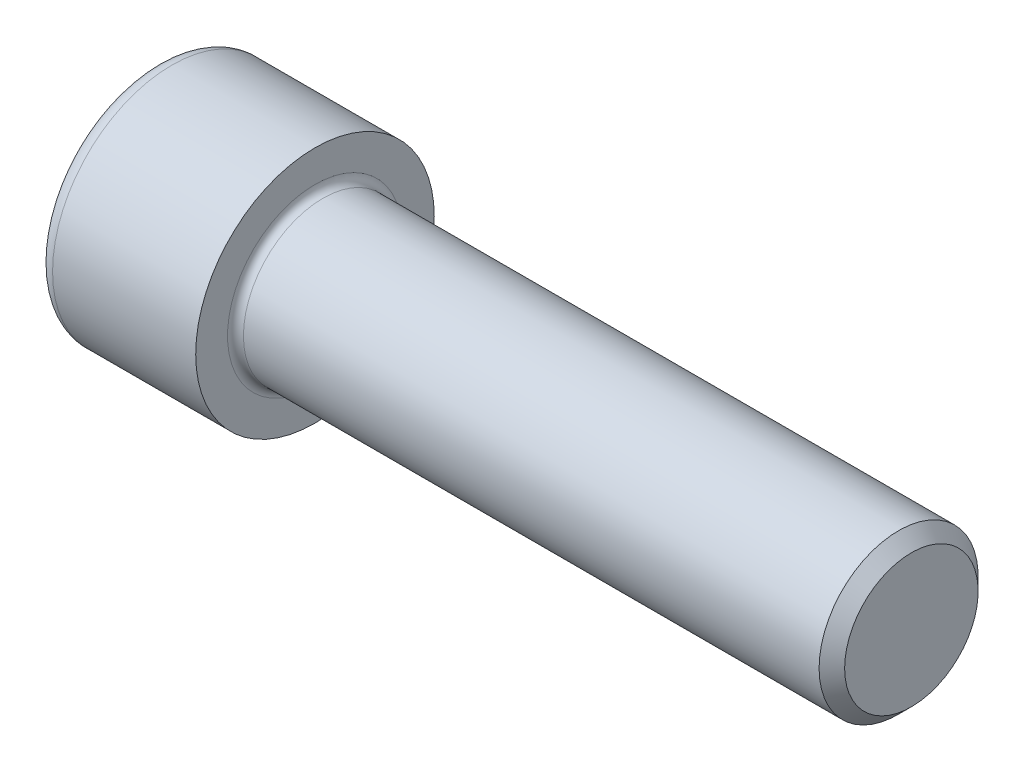
SolidWorks part; units mm, degrees
ref_plane "Plane1" through (0, 0, 0) normal (0, 0, 1) x (1, 0, 0)
ref_plane "Plane2" through (0, 0, 0) normal (0, 1, 0) x (1, 0, 0)
ref_plane "Plane3" through (0, 0, 0) normal (1, 0, 0) x (0, 0, -1)
sketch "BodySke" plane through (0, 0, 0) normal (0, 0, 1) x (1, 0, 0)
  line L0 (0, 0) -> (0, 9)
  line L1 (0, 9) -> (12, 9)
  line L2 (12, 9) -> (12, 6)
  line L3 (12, 6) -> (56.036, 6)
  line L4 (57, 5.036) -> (57, 0)
  line L5 (57, 0) -> (0, 0)
  line L6 (-31.75, 0) -> (127, 0) construction
  line L8 (57, 5.036) -> (56.036, 6)
  line L10 (57, -5.036) -> (56.036, -6) construction
  line L11 (13.75, 9.525) -> (13.75, 3.175) construction
  line L12 (12, 9.525) -> (12, 3.175) construction
  line L13 (-3, 9.525) -> (-3, 3.175) construction
  dimension "Diameter" = 12
  dimension "Head_ht" = 12
  dimension "Length" = 45
  dimension "Body_ch_ang" = 45
  dimension "Head_dia" = 18
  dimension "Minor_dia" = 10.072
  dimension "Advance" = 1.75
  dimension "Thread_nom" = 45
  dimension "Thread_length" = 60
revolve "Base-Revolve" add sketch "BodySke"
cosmetic thread "ThreadCosmetic" [suppressed]
fillet "Fillet1" radius 0.6 1 edges at (12, 0, 6)
fillet "Fillet2" radius 1.2 1 edges at (0, 0, 9)
sketch "Sketch2" plane through (0, 0, 0) normal (0, 0, 1) x (1, 0, 0)
  line L0 (0, 5.0125) -> (6, 5.0125)
  line L1 (6, 5.0125) -> (8.894, 0)
  line L2 (-31.75, 0) -> (127, 0) construction
  line L3 (8.894, 0) -> (0, 0)
  line L4 (0, 0) -> (0, 5.0125)
  line L6 (0, 0) -> (47.625, 0) construction
  dimension "D1" = 5.0125
  dimension "D2" = 60
  dimension "Depth" = 6
revolve "Hex-PreBroach" cut sketch "Sketch2" angle 360 about L6
sketch "Sketch3" plane through (0, 0, 0) normal (-1, 0, 0) x (0, 0.5, 0.866)
  line L0 (2.894, 5.0125) -> (-2.894, 5.0125)
  line L1 (-2.894, 5.0125) -> (-5.7879, 0)
  line L2 (2.894, 5.0125) -> (5.7879, 0)
  line L3 (2.894, -5.0125) -> (5.7879, 0)
  line L4 (2.894, -5.0125) -> (-2.894, -5.0125)
  line L5 (-2.894, -5.0125) -> (-5.7879, 0)
  dimension "D1" = 5.0125
  dimension "D2" = 5.0125
  dimension "Hex_size" = 10.025
extrude "Hex" cut sketch "Sketch3" against normal blind 6
sketch "ThdSchSke" plane through (0, 0, 0) normal (0, 0, 1) x (1, 0, 0)
  line L0 (17.25, -5.036) -> (16.575, -6)
  line L1 (17.25, -5.036) -> (17.925, -6)
  line L2 (17.925, -6) -> (17.925, -7.5)
  line L3 (-3.175, 0) -> (5.1513, 0) construction
  line L4 (0, 7.8) -> (0, -7.8) construction
  line L5 (17.925, -7.5) -> (16.575, -7.5)
  line L6 (16.575, -7.5) -> (16.575, -6)
  dimension "Thread_minor" = 10.072
  dimension "Diameter" = 12
  dimension "Start" = 17.25
  dimension "SideAngle" = 55
  dimension "VeeAngle" = 70
  dimension "Overcut" = 15
revolve "ThreadSchematic" [suppressed] cut sketch "ThdSchSke" angle 360 about L3
pattern_linear "ThdSchPat" [suppressed]
equation "\"D2@Sketch3\" = \"Hex_size@Sketch3\" / 2"
equation "\"D1@Sketch3\" = \"Hex_size@Sketch3\" / 2"
equation "\"D1@Sketch2\" = \"Hex_size@Sketch3\" / 2"
equation "\"Thread_minor@ThreadCosmetic\"  =  \"Minor_dia@BodySke\""
equation "\"Depth@Sketch2\" =  \"Key_eng@Hex\""
equation "\"Thread_length@ThreadCosmetic\" = ((sgn( (\"Length@BodySke\" - \"Advance@BodySke\" * 3.0) - \"Thread_nom@BodySke\" )-1)*( (\"Length@BodySke\" - \"Advance@BodySke\" * 3.0) - \"Thread_nom@BodySke\" ))/-2+ \"Thread_nom@BodySke\""
equation "\"Thread_minor@ThdSchSke\" = \"Minor_dia@BodySke\""
equation "\"Diameter@ThdSchSke\" = \"Diameter@BodySke\""
equation "\"Overcut@ThdSchSke\" = \"Diameter@BodySke\" * 1.25"
equation "\"Start@ThdSchSke\" = \"Head_ht@BodySke\" + \"Length@BodySke\" - \"Thread_length@ThreadCosmetic\"  '---Non-countersunk---"
equation "\"Num_threads@ThdSchPat\" = int( \"Thread_length@ThreadCosmetic\" / \"Advance@BodySke\" + 0.999 )  + 1"
equation "\"Advance@ThdSchPat\" = \"Thread_length@ThreadCosmetic\" /  (\"Num_threads@ThdSchPat\" - 1) 'relax it"
equation "\"Num_threads@ThdSchPat\" = \"Num_threads@ThdSchPat\" - sgn( \"Num_threads@ThdSchPat\" - 1) '---chamfered tips only---"
